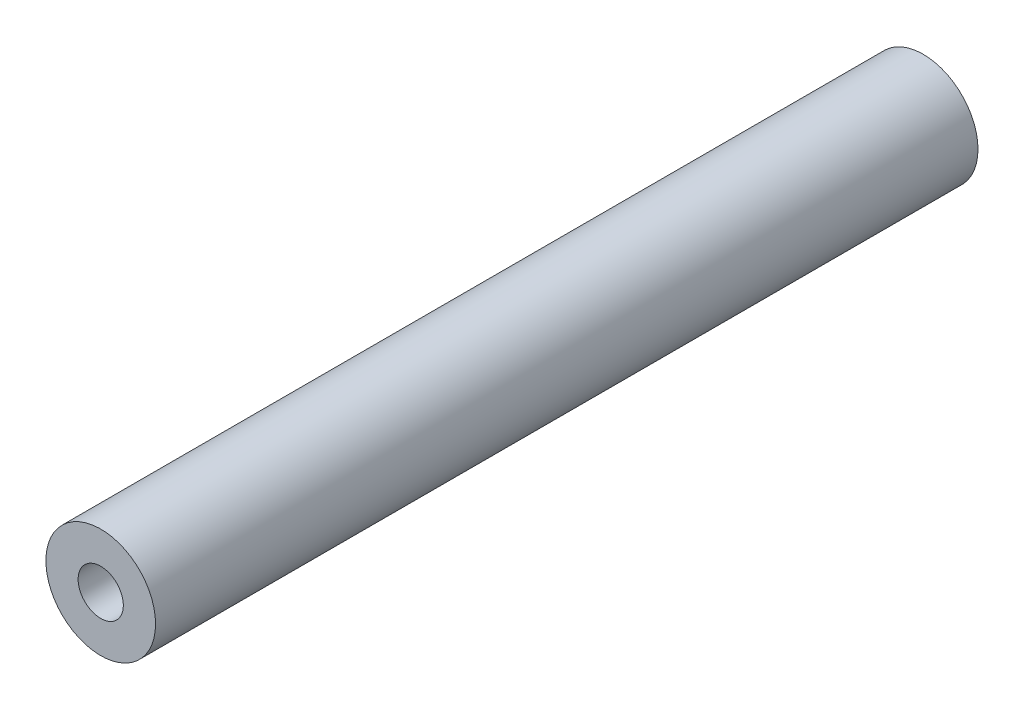
SolidWorks part; units mm, degrees
ref_plane "Front Plane" through (0, 0, 0) normal (0, 0, 1) x (1, 0, 0)
ref_plane "Top Plane" through (0, 0, 0) normal (0, 1, 0) x (1, 0, 0)
ref_plane "Right Plane" through (0, 0, 0) normal (1, 0, 0) x (0, 0, -1)
sketch "Sketch1" plane through (0, 0, 0) normal (0, 0, 1) x (1, 0, 0)
  circle A0 centre (0, 0) radius 4
extrude "Boss-Extrude1" add sketch "Sketch1" along normal blind 60
hole_wizard "M4x0.7 Tapped Hole1" positions "Sketch3" profile "Sketch2" tap size "M4x0.7" standard "ANSI Metric"
sketch "Sketch3" plane through (0, 0, 60) normal (0, 0, 1) x (1, 0, 0)
  point P0 (0, 0)
sketch "Sketch2" plane through (0, 0, 60) normal (1, 0, 0) x (0, -1, 0)
  line L0 (0, 0) -> (0, 10.0914)
  line L1 (0, 10.0914) -> (1.65, 9.1)
  line L2 (1.65, 9.1) -> (1.65, 0)
  line L5 (1.65, 0) -> (0, 0)
  line L10 (0, 10.0914) -> (-1.65, 9.1) construction
  line L11 (0, -6.35) -> (0, 107.95) construction
  dimension "Tap Drill Dia." = 3.3
  dimension "Tap Drill Depth" = 9.1
  dimension "Drill Angle" = 118
hole_wizard "M4x0.7 Tapped Hole2" positions "Sketch5" profile "Sketch4" tap size "M4x0.7" standard "ANSI Metric"
sketch "Sketch5" plane through (0, 0, 0) normal (0, 0, -1) x (-1, 0, 0)
  point P0 (0, 0)
sketch "Sketch4" plane through (0, 0, 0) normal (1, 0, 0) x (0, 1, 0)
  line L0 (0, 0) -> (0, 10.0914)
  line L1 (0, 10.0914) -> (1.65, 9.1)
  line L2 (1.65, 9.1) -> (1.65, 0)
  line L5 (1.65, 0) -> (0, 0)
  line L10 (0, 10.0914) -> (-1.65, 9.1) construction
  line L11 (0, -6.35) -> (0, 107.95) construction
  dimension "Tap Drill Dia." = 3.3
  dimension "Tap Drill Depth" = 9.1
  dimension "Drill Angle" = 118
